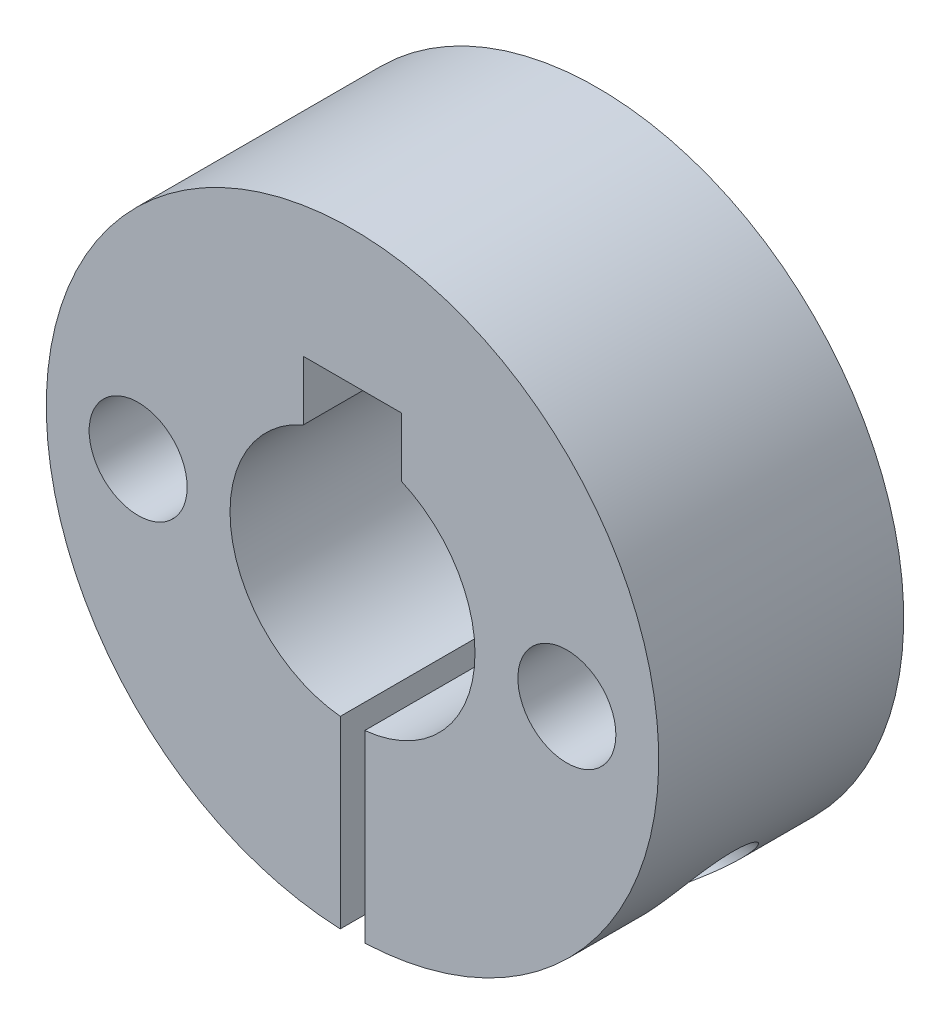
SolidWorks part; units mm, degrees
material "6061-T6 (SS)"
ref_plane "Front Plane" through (0, 0, 0) normal (0, 0, 1) x (1, 0, 0)
ref_plane "Top Plane" through (0, 0, 0) normal (0, 1, 0) x (1, 0, 0)
ref_plane "Right Plane" through (0, 0, 0) normal (1, 0, 0) x (0, 0, -1)
sketch "Sketch1" plane through (0, 0, 0) normal (0, 0, 1) x (1, 0, 0)
  circle A0 centre (0, 0) radius 10
  circle A1 centre (0, 0) radius 25
  dimension "D1" = 20
  dimension "D2" = 15
extrude "Boss-Extrude1" add sketch "Sketch1" along normal mid plane 20
sketch "Sketch2" plane through (0, 0, 10) normal (0, 0, 1) x (1, 0, 0)
  line L0 (0, 10) -> (0, 0) construction
  line L1 (-4, 14) -> (4, 14)
  line L2 (-4, 14) -> (-4, 6)
  line L3 (-4, 6) -> (4, 6)
  line L4 (4, 14) -> (4, 6)
  line L5 (-4, 14) -> (4, 6) construction
  line L6 (-4, 6) -> (4, 14) construction
  line L7 (0, -10) -> (0, -25) construction
  line L8 (10, 0) -> (25, 0) construction
  line L9 (-1, -27.5) -> (1, -27.5)
  line L10 (-1, -27.5) -> (-1, -7.5)
  line L11 (-1, -7.5) -> (1, -7.5)
  line L12 (1, -27.5) -> (1, -7.5)
  line L13 (-1, -27.5) -> (1, -7.5) construction
  line L14 (-1, -7.5) -> (1, -27.5) construction
  line L15 (-10, 0) -> (-25, 0) construction
  circle A0 centre (0, 0) radius 10 construction
  circle A1 centre (17.5, 0) radius 4
  circle A2 centre (0, 0) radius 25 construction
  circle A3 centre (-17.5, 0) radius 4
  point P0 (0, 10)
  point P15 (0, -17.5)
  dimension "D5" = 8
  dimension "D1" = 8
  dimension "D2" = 8
  dimension "D3" = 20
  dimension "D4" = 2
extrude "Cut-Extrude1" cut sketch "Sketch2" against normal through all both and the other way through all
sketch "Sketch3" plane through (0, 0, 0) normal (1, 0, 0) x (0, 0, -1)
  line L0 (0, -9.9499) -> (0, -24.98) construction
  line L4 (10, -24.98) -> (10, -9.9499)
  line L5 (10, -9.9499) -> (-10, -9.9499)
  line L6 (-10, -9.9499) -> (-10, -24.98)
  line L7 (-10, -24.98) -> (10, -24.98)
  line L9 (10, -9.9499) -> (-10, -9.9499) construction
  line L11 (-10, -24.98) -> (10, -24.98) construction
  circle A0 centre (0, -17.4649) radius 4
  dimension "D2" = 8
  dimension "D1" = 0
extrude "Cut-Extrude2" cut sketch "Sketch3" against normal through all both and the other way through all
sketch "Sketch5" plane through (0, 0, 0) normal (1, 0, 0) x (0, 0, -1)
  circle A0 centre (0, -17.4649) radius 6.75
  dimension "D1" = 13.5
extrude "Cut-Extrude4" cut sketch "Sketch5" against normal through all from offset 7 offset against normal yes
sketch "Sketch6" plane through (0, 0, 0) normal (1, 0, 0) x (0, 0, -1)
  line L0 (-10, 0.01) -> (10, 0.01) construction
  line L1 (-10, 25) -> (-10, -24.98) construction
  line L2 (10, -24.98) -> (10, 25) construction
  line L3 (0, -25) -> (0, 25) construction
  line L4 (10, 25) -> (-10, 25) construction
  point P12 (0, 0)
